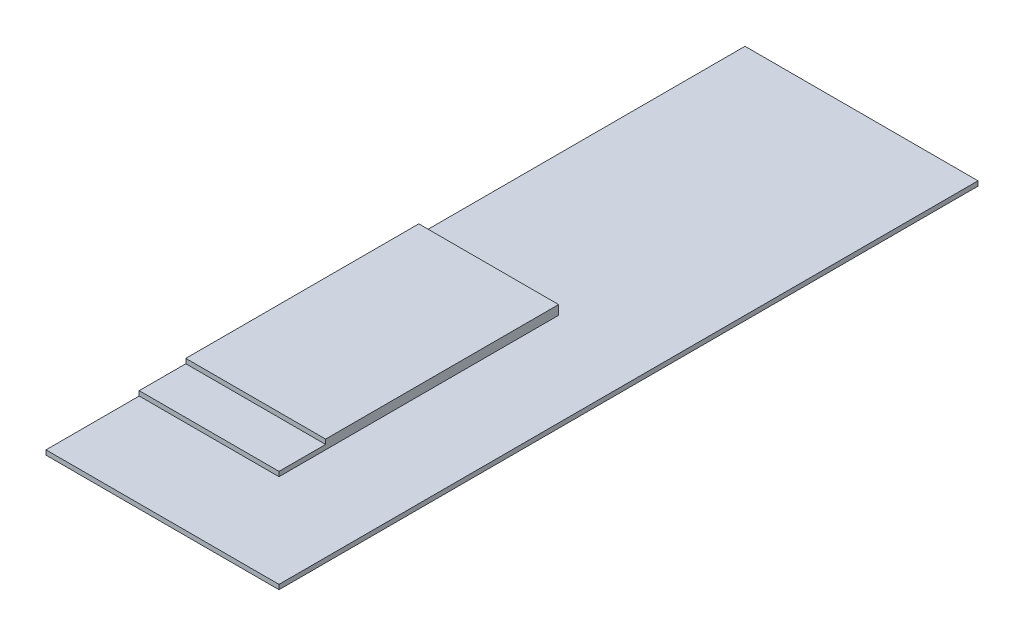
SolidWorks part; units mm, degrees
ref_plane "Alzado" through (0, 0, 0) normal (0, 0, 1) x (1, 0, 0)
ref_plane "Planta" through (0, 0, 0) normal (0, 1, 0) x (1, 0, 0)
ref_plane "Vista lateral" through (0, 0, 0) normal (1, 0, 0) x (0, 0, -1)
sketch "Croquis1" plane through (0, 0, 0) normal (0, 1, 0) x (1, 0, 0)
  line L0 (-1563.6364, 2218.1818) -> (-1563.6364, -5781.8182) construction
  line L1 (-2563.6364, 2218.1818) -> (436.3636, 2218.1818)
  line L2 (-2563.6364, 2218.1818) -> (-2563.6364, -5781.8182)
  line L3 (-2563.6364, -5781.8182) -> (436.3636, -5781.8182)
  line L4 (436.3636, 2218.1818) -> (436.3636, -5781.8182)
  line L5 (-563.6364, 2218.1818) -> (-563.6364, -5781.8182) construction
  dimension "D1" = 3000
  dimension "D2" = 8000
  dimension "D3" = 1000
  dimension "D4" = 1000
extrude "Saliente-Extruir1" add sketch "Croquis1" along normal blind 100
sketch "Croquis2" plane through (0, 100, 0) normal (0, 1, 0) x (1, 0, 0)
  line L0 (-2563.6364, -3781.8182) -> (436.3636, -3781.8182) construction
  line L1 (-2563.6364, 2218.1818) -> (-2563.6364, -5781.8182) construction
  line L2 (436.3636, -5781.8182) -> (436.3636, 2218.1818) construction
  line L3 (-2563.6364, -2781.8182) -> (436.3636, -2781.8182) construction
  line L4 (436.3636, 2218.1818) -> (-2563.6364, 2218.1818) construction
  line L6 (-2563.6364, -3781.8182) -> (436.3636, -3781.8182)
  line L7 (-2563.6364, -3781.8182) -> (-2563.6364, 2218.1818)
  line L8 (-2563.6364, 2218.1818) -> (436.3636, 2218.1818)
  line L9 (436.3636, -3781.8182) -> (436.3636, 2218.1818)
  dimension "D1" = 5000
  dimension "D2" = 1000
extrude "Saliente-Extruir2" add sketch "Croquis2" along normal blind 100
sketch "Croquis3" plane through (0, 200, 0) normal (0, 1, 0) x (1, 0, 0)
  line L0 (436.3636, -3781.8182) -> (436.3636, 2218.1818) construction
  line L1 (-2563.6364, 2218.1818) -> (436.3636, 2218.1818)
  line L2 (-2563.6364, 2218.1818) -> (-2563.6364, -2781.8182)
  line L3 (-2563.6364, -2781.8182) -> (436.3636, -2781.8182)
  line L4 (436.3636, 2218.1818) -> (436.3636, -2781.8182)
  dimension "D1" = 5000
extrude "Saliente-Extruir3" add sketch "Croquis3" along normal blind 100
sketch "Croquis4" plane through (0, 300, 0) normal (0, 1, 0) x (1, 0, 0)
  line L0 (436.3636, 2218.1818) -> (-2563.6364, 2218.1818) construction
  circle A0 centre (-2040.8464, 1718.1818) radius 150
  circle A1 centre (-996.2426, 1718.1818) radius 150
  circle A2 centre (0, 1718.1818) radius 150
  circle A3 centre (-2040.8464, 718.1818) radius 150
  circle A4 centre (-996.2426, 718.1818) radius 150
  circle A5 centre (0, 718.1818) radius 150
  circle A6 centre (-2040.8464, -281.8182) radius 150
  circle A7 centre (-996.2426, -281.8182) radius 150
  circle A8 centre (0, -281.8182) radius 150
  circle A9 centre (-2040.8464, -1281.8182) radius 150
  circle A10 centre (-996.2426, -1281.8182) radius 150
  circle A11 centre (0, -1281.8182) radius 150
  circle A12 centre (-2040.8464, -2281.8182) radius 150
  circle A13 centre (-996.2426, -2281.8182) radius 150
  circle A14 centre (0, -2281.8182) radius 150
  dimension "D1" = 300
  dimension "D2" = 500
sketch "Croquis5" plane through (0, 100, 0) normal (0, 1, 0) x (1, 0, 0)
  line L1 (-2563.6364, -5781.8182) -> (2436.3636, -5781.8182)
  line L2 (-2563.6364, -5781.8182) -> (-2563.6364, 9218.1818)
  line L3 (-2563.6364, 9218.1818) -> (2436.3636, 9218.1818)
  line L4 (2436.3636, -5781.8182) -> (2436.3636, 9218.1818)
  dimension "D1" = 15000
  dimension "D2" = 5000
extrude "Saliente-Extruir4" add sketch "Croquis5" against normal blind 100
